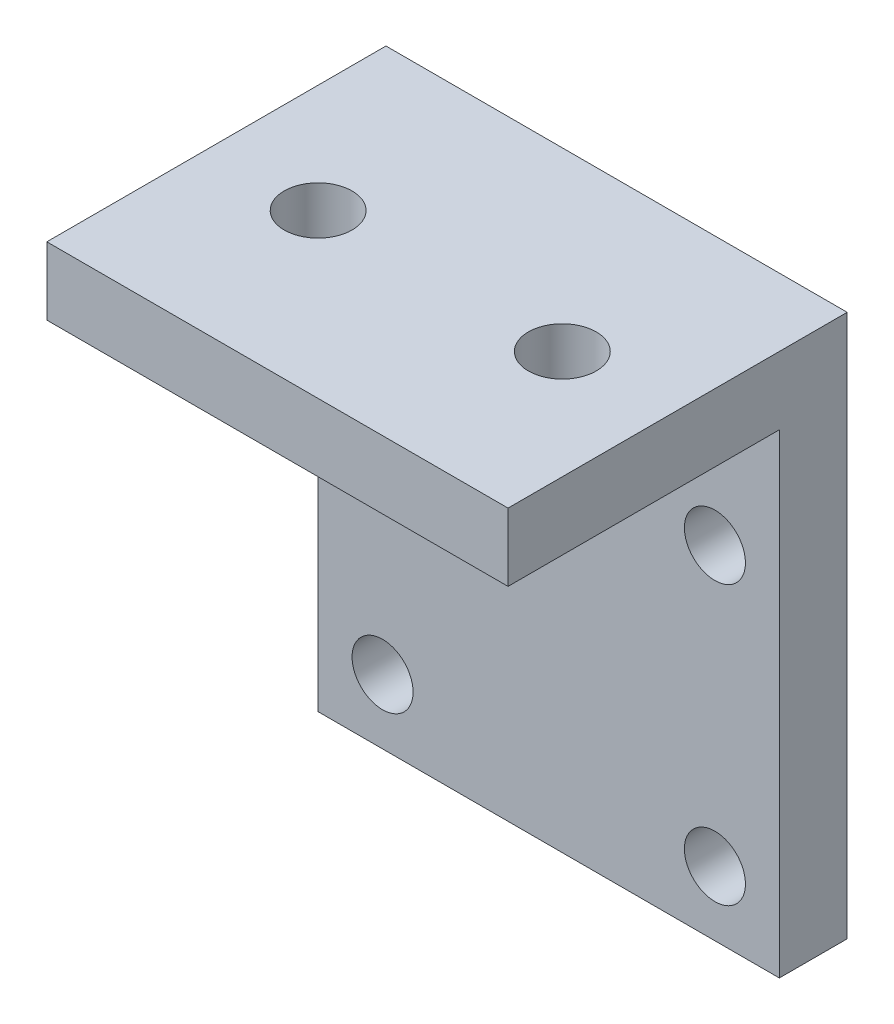
SolidWorks part; units mm, degrees
ref_plane "Front Plane" through (0, 0, 0) normal (0, 0, 1) x (1, 0, 0)
ref_plane "Top Plane" through (0, 0, 0) normal (0, 1, 0) x (1, 0, 0)
ref_plane "Right Plane" through (0, 0, 0) normal (1, 0, 0) x (0, 0, -1)
sketch "Sketch1" plane through (0, 0, 0) normal (0, 0, 1) x (1, 0, 0)
  line L1 (0, 0) -> (34, 0)
  line L2 (0, 0) -> (0, 30)
  line L3 (0, 30) -> (34, 30)
  line L4 (34, 0) -> (34, 30)
  circle A0 centre (4.75, 25.25) radius 2.25
  circle A1 centre (29.25, 25.25) radius 2.25
  circle A2 centre (29.25, 4.75) radius 2.25
  circle A3 centre (4.75, 4.75) radius 2.25
  dimension "D3" = 4.5
  dimension "D6" = 4.5
  dimension "D13" = 4.5
  dimension "D14" = 4.5
  dimension "D1" = 30
  dimension "D2" = 34
  dimension "D4" = 4.75
  dimension "D5" = 4.75
  dimension "D7" = 4.75
  dimension "D8" = 4.75
  dimension "D9" = 4.75
  dimension "D10" = 4.75
  dimension "D11" = 4.75
  dimension "D12" = 4.75
extrude "Boss-Extrude1" add sketch "Sketch1" along normal blind 5
sketch "Sketch2" plane through (0, 30, 0) normal (0, 1, 0) x (1, 0, 0)
  line L1 (0, 0) -> (34, 0)
  line L2 (0, 0) -> (0, -5)
  line L3 (0, -5) -> (34, -5)
  line L4 (34, 0) -> (34, -5)
extrude "Boss-Extrude2" add sketch "Sketch2" along normal blind 10
sketch "Sketch3" plane through (0, 0, 5) normal (0, 0, 1) x (1, 0, 0)
  line L0 (34, 0) -> (34, 40) construction
  line L1 (0, 40) -> (34, 40)
  line L2 (0, 40) -> (0, 35)
  line L3 (0, 35) -> (34, 35)
  line L4 (34, 40) -> (34, 35)
  dimension "D1" = 5
extrude "Boss-Extrude3" add sketch "Sketch3" along normal blind 20
sketch "Sketch4" plane through (0, 40, 0) normal (0, 1, 0) x (1, 0, 0)
  line L0 (34, -25) -> (34, 0) construction
  line L2 (34, -25) -> (0, -25) construction
  circle A0 centre (8, -13) radius 2.5
  circle A1 centre (26, -13) radius 2.5
  dimension "D1" = 5
  dimension "D2" = 5
  dimension "D3" = 18
  dimension "D4" = 8
  dimension "D5" = 0
  dimension "D6" = 12
extrude "Cut-Extrude1" cut sketch "Sketch4" against normal blind 20
